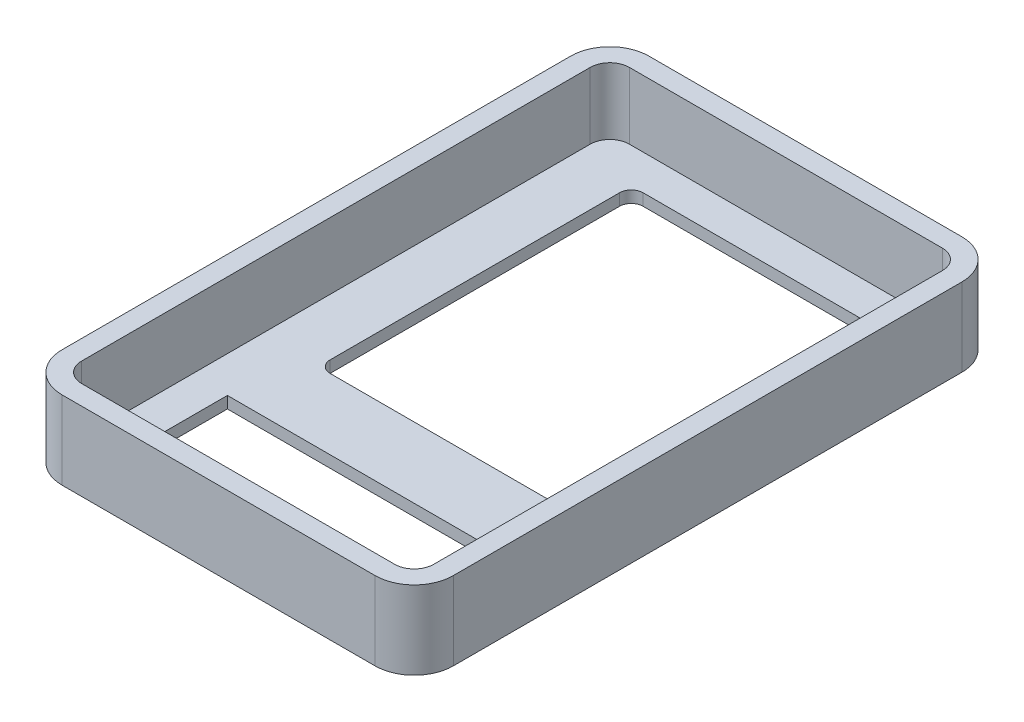
SolidWorks part; units mm, degrees
ref_plane "Front Plane" through (0, 0, 0) normal (0, 0, 1) x (1, 0, 0)
ref_plane "Top Plane" through (0, 0, 0) normal (0, 1, 0) x (1, 0, 0)
ref_plane "Right Plane" through (0, 0, 0) normal (1, 0, 0) x (0, 0, -1)
sketch "Sketch1" plane through (0, 0, 0) normal (0, 1, 0) x (1, 0, 0)
  line L0 (-45, -65) -> (-45, 65)
  line L5 (-40, -75) -> (40, -75)
  line L6 (-50, -65) -> (-50, 65)
  line L7 (-40, 75) -> (40, 75)
  line L8 (50, -65) -> (50, 65)
  line L9 (-50, -75) -> (50, 75) construction
  line L10 (-50, 75) -> (50, -75) construction
  line L11 (-40, 70) -> (40, 70)
  line L12 (45, -65) -> (45, 65)
  line L13 (-40, -70) -> (40, -70)
  arc A0 (50, 65) -> (40, 75) centre (40, 65) ccw
  arc A1 (50, -65) -> (40, -75) centre (40, -65) cw
  arc A2 (-50, -65) -> (-40, -75) centre (-40, -65) ccw
  arc A3 (-50, 65) -> (-40, 75) centre (-40, 65) cw
  arc A4 (-45, 65) -> (-40, 70) centre (-40, 65) cw
  arc A5 (45, 65) -> (40, 70) centre (40, 65) ccw
  arc A6 (45, -65) -> (40, -70) centre (40, -65) cw
  arc A7 (-45, -65) -> (-40, -70) centre (-40, -65) ccw
  point P0 (0, 0)
  dimension "D3" = 10
  dimension "D1" = 100
  dimension "D2" = 150
  dimension "D4" = 5
extrude "Boss-Extrude1" add sketch "Sketch1" along normal blind 20 contours A3 L6 A2 L5 A1 L8 A0 L7
sketch "Sketch3" plane through (0, 20, 0) normal (0, 1, 0) x (1, 0, 0)
  line L8 (40, 70) -> (-40, 70)
  line L9 (-45, 65) -> (-45, -65)
  line L10 (-40, -70) -> (40, -70)
  line L11 (45, -65) -> (45, 65)
  line L12 (40, 70) -> (-40, 70)
  line L13 (-45, 65) -> (-45, -65)
  line L14 (-40, -70) -> (40, -70)
  line L15 (45, -65) -> (45, 65)
  arc A8 (-40, 70) -> (-45, 65) centre (-40, 65) ccw
  arc A9 (-45, -65) -> (-40, -70) centre (-40, -65) ccw
  arc A10 (40, -70) -> (45, -65) centre (40, -65) ccw
  arc A11 (45, 65) -> (40, 70) centre (40, 65) ccw
  arc A12 (-40, 70) -> (-45, 65) centre (-40, 65) ccw
  arc A13 (-45, -65) -> (-40, -70) centre (-40, -65) ccw
  arc A14 (40, -70) -> (45, -65) centre (40, -65) ccw
  arc A15 (45, 65) -> (40, 70) centre (40, 65) ccw
  dimension "D1" = 5
extrude "Cut-Extrude1" cut sketch "Sketch3" against normal blind 17
sketch "Sketch4" plane through (0, 0, 0) normal (0, -1, 0) x (1, 0, 0)
  line L0 (-50, 65) -> (-50, -65) construction
  line L1 (-27.5, -61) -> (27.5, -61)
  line L2 (-30.5, -58) -> (-30.5, 16)
  line L3 (-27.5, 19) -> (27.5, 19)
  line L4 (30.5, -58) -> (30.5, 16)
  line L5 (50, 65) -> (50, -65) construction
  line L6 (-40, -75) -> (40, -75) construction
  line L8 (-35.75, 63.25) -> (35.75, 63.25)
  line L9 (-35.75, 63.25) -> (-35.75, 37)
  line L10 (-35.75, 37) -> (35.75, 37)
  line L11 (35.75, 63.25) -> (35.75, 37)
  line L13 (-40, 75) -> (40, 75) construction
  arc A0 (27.5, 19) -> (30.5, 16) centre (27.5, 16) cw
  arc A1 (27.5, -61) -> (30.5, -58) centre (27.5, -58) ccw
  arc A2 (-27.5, -61) -> (-30.5, -58) centre (-27.5, -58) cw
  arc A3 (-30.5, 16) -> (-27.5, 19) centre (-27.5, 16) cw
  point P12 (30.5, 19)
  point P15 (30.5, -61)
  point P20 (-30.5, 19)
  dimension "D6" = 3
  dimension "D1" = 80
  dimension "D2" = 61
  dimension "D3" = 19.5
  dimension "D4" = 19.5
  dimension "D5" = 14
  dimension "D7" = 71.5
  dimension "D8" = 18
  dimension "D9" = 26.25
  dimension "D10" = 14.25
  dimension "D11" = 14.25
  dimension "D12" = 11.75
extrude "Cut-Extrude2" cut sketch "Sketch4" against normal through all
